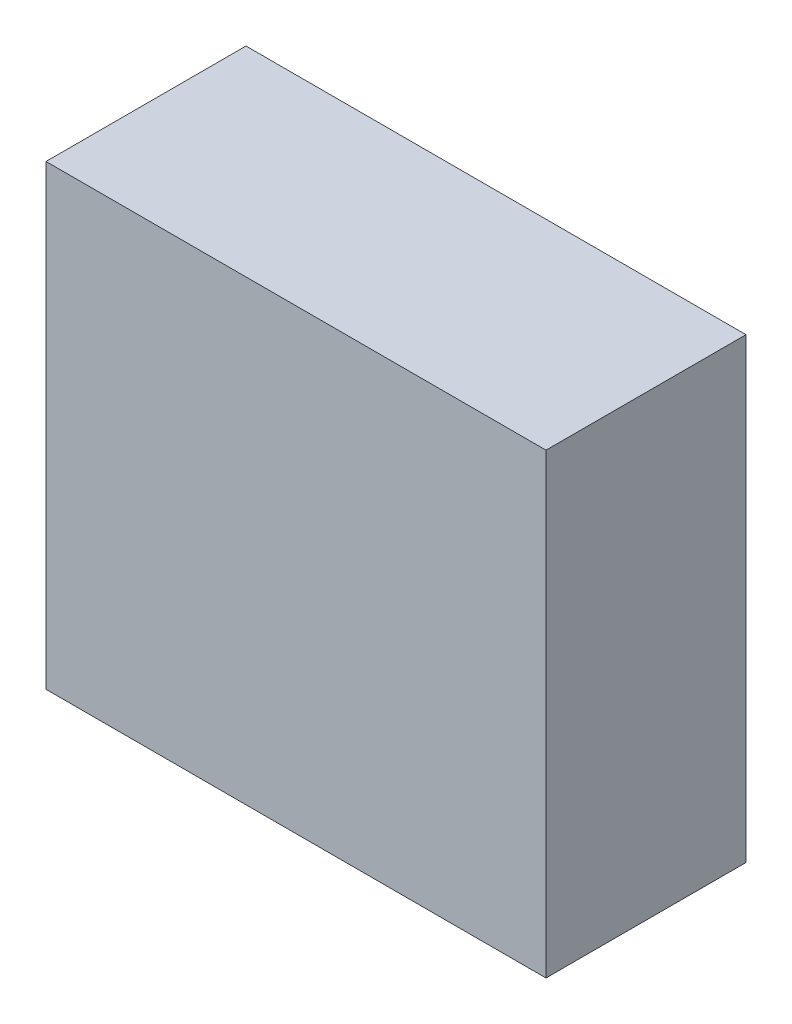
SolidWorks part; units mm, degrees
ref_plane "前视基准面" through (0, 0, 0) normal (0, 0, 1) x (1, 0, 0)
ref_plane "上视基准面" through (0, 0, 0) normal (0, 1, 0) x (1, 0, 0)
ref_plane "右视基准面" through (0, 0, 0) normal (1, 0, 0) x (0, 0, -1)
sketch "草图1" plane through (0, 0, 0) normal (0, 0, 1) x (1, 0, 0)
  line L0 (-1.75, 1.6) -> (1.75, 1.6)
  line L1 (1.75, 1.6) -> (1.75, -1.6)
  line L2 (1.75, -1.6) -> (-1.75, -1.6)
  line L3 (-1.75, -1.6) -> (-1.75, 1.6)
extrude "Component_Outline" add sketch "草图1" along normal blind 1.4 separate body
sketch3d "3D草图1"
  line L0 (0, 0, 0) -> (1, 0, 0)
  line L1 (0, 0, 0) -> (0, 1, 0)
  line L2 (0, 0, 0) -> (0, 0, 1)
  point P0 (0, 0, 0)
